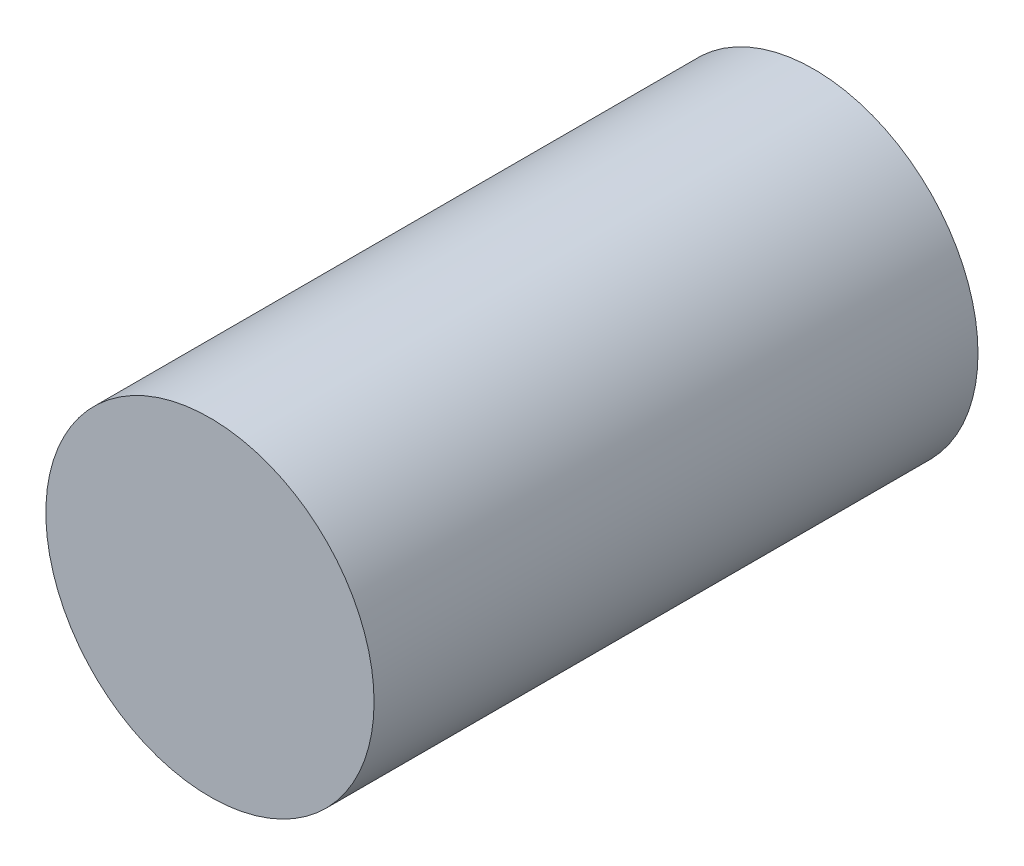
SolidWorks part; units mm, degrees
ref_plane "Front" through (0, 0, 0) normal (0, 0, 1) x (1, 0, 0)
ref_plane "Top" through (0, 0, 0) normal (0, 1, 0) x (1, 0, 0)
ref_plane "Right" through (0, 0, 0) normal (1, 0, 0) x (0, 0, -1)
sketch "Sketch1" plane through (0, 0, 0) normal (0, 0, 1) x (1, 0, 0)
  circle A0 centre (0, 0) radius 12.5
  dimension "D1" = 25
extrude "Boss-Extrude1" add sketch "Sketch1" along normal blind 46 contours A0
